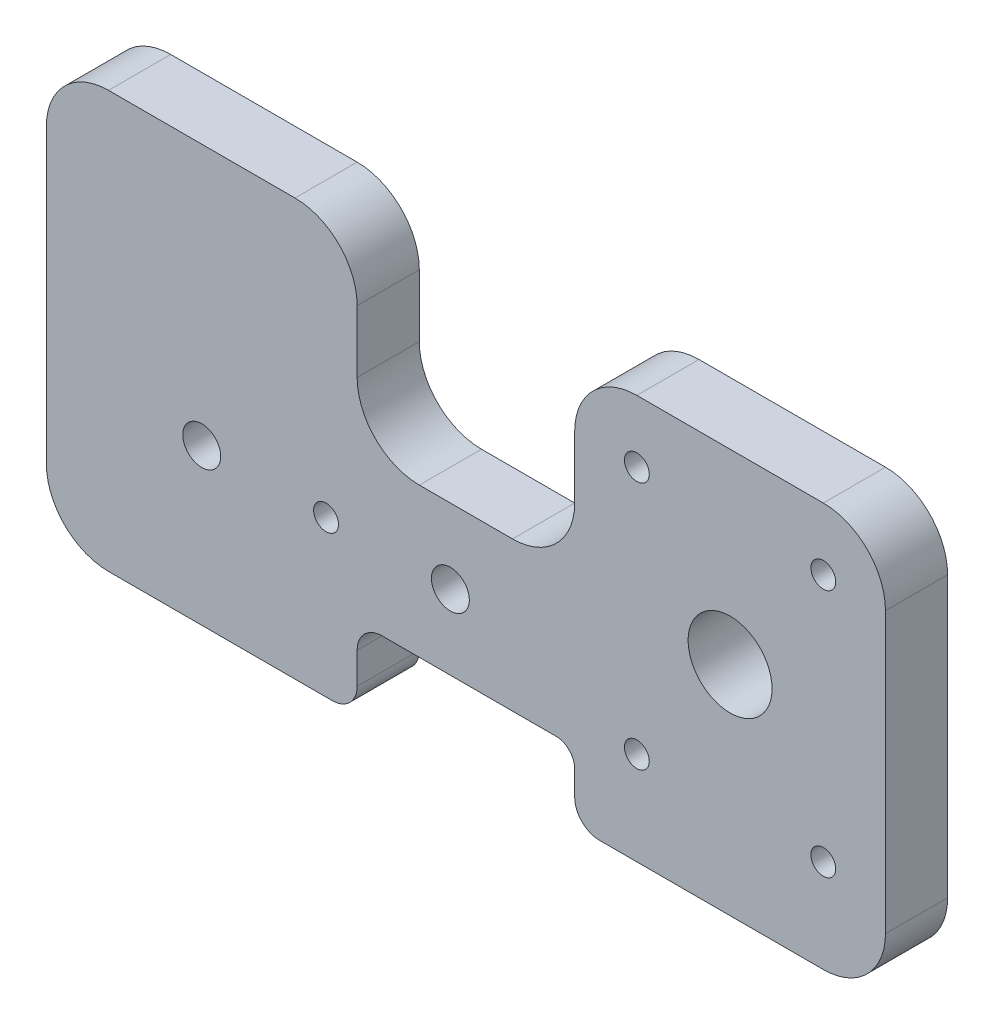
SolidWorks part; units mm, degrees
ref_plane "Front Plane" through (0, 0, 0) normal (0, 0, 1) x (1, 0, 0)
ref_plane "Top Plane" through (0, 0, 0) normal (0, 1, 0) x (1, 0, 0)
ref_plane "Right Plane" through (0, 0, 0) normal (1, 0, 0) x (0, 0, -1)
sketch "Model" plane through (0, 0, 0) normal (0, 0, 1) x (1, 0, 0)
  line L0 (106.9106, -1) -> (106.9106, 3)
  line L1 (75.9106, 6) -> (103.9106, 6)
  line L2 (71.9106, 2) -> (71.9106, -3.0349)
  line L3 (67.9106, -7.0349) -> (31.9106, -7.0349)
  line L4 (21.9106, 2.9651) -> (21.9106, 50)
  line L5 (31.9106, 60) -> (61.9106, 60)
  line L6 (71.9106, 50) -> (71.9106, 40)
  line L7 (96.9106, 30) -> (81.9106, 30)
  line L8 (106.9106, 50) -> (106.9106, 40)
  line L9 (146.9106, 60) -> (116.9106, 60)
  line L10 (156.9106, 5) -> (156.9106, 50)
  line L11 (146.9106, -5) -> (110.9106, -5)
  circle A0 centre (66.9106, 18) radius 2
  circle A1 centre (46.9106, 18) radius 3.05
  circle A2 centre (116.9106, 10) radius 2
  circle A3 centre (146.9106, 10) radius 2
  circle A4 centre (146.9106, 50) radius 2
  circle A5 centre (116.9106, 50) radius 2
  circle A6 centre (131.9106, 30) radius 6.75
  circle A7 centre (86.9106, 18) radius 3.05
  arc A8 (106.9106, -1) -> (110.9106, -5) centre (110.9106, -1) ccw
  arc A9 (106.9106, 3) -> (103.9106, 6) centre (103.9106, 3) ccw
  arc A10 (75.9106, 6) -> (71.9106, 2) centre (75.9106, 2) ccw
  arc A11 (67.9106, -7.0349) -> (71.9106, -3.0349) centre (67.9106, -3.0349) ccw
  arc A12 (21.9106, 2.9651) -> (31.9106, -7.0349) centre (31.9106, 2.9651) ccw
  arc A13 (31.9106, 60) -> (21.9106, 50) centre (31.9106, 50) ccw
  arc A14 (71.9106, 50) -> (61.9106, 60) centre (61.9106, 50) ccw
  arc A15 (71.9106, 40) -> (81.9106, 30) centre (81.9106, 40) ccw
  arc A16 (96.9106, 30) -> (106.9106, 40) centre (96.9106, 40) ccw
  arc A17 (116.9106, 60) -> (106.9106, 50) centre (116.9106, 50) ccw
  arc A18 (156.9106, 50) -> (146.9106, 60) centre (146.9106, 50) ccw
  arc A19 (146.9106, -5) -> (156.9106, 5) centre (146.9106, 5) ccw
extrude "Boss-Extrude1" add sketch "Model" along normal blind 10
sketch "Sketch2" plane through (0, 0, 10) normal (0, 0, 1) x (1, 0, 0)
  text T0 "Copyright © Adarsh Belavatagi and Manikanta Pujar 2018.\r\nThis documentation describes Open Hardware and is licensed under the CERN OHL v. 1.2.\r\nYou may redistribute and modify this documentation under the terms of the CERN OHL v.1.2.\r\n(http://ohwr.org/cernohl). This documentation is distributed WITHOUT ANY EXPRESS OR\r\nIMPLIED WARRANTY, INCLUDING OF MERCHANTABILITY, SATISFACTORY QUALITY AND FITNESS FOR A PARTICULAR PURPOSE.\r\nPlease see the CERN OHL v.1.2 for applicable conditions\r\n\r\nThe full text of the license is available in LICENSE.txt(https://github.com/AdarshBelavatagi/Maudslay/blob/master/LICENSE.txt)\r\n\r\n"
